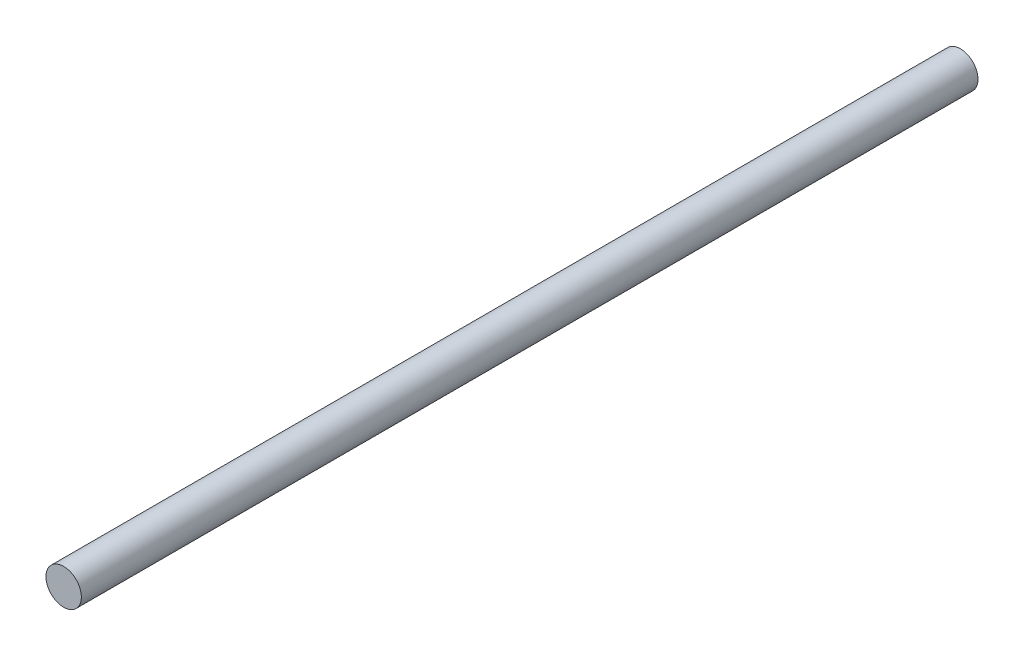
SolidWorks part; units mm, degrees
ref_plane "Front Plane" through (0, 0, 0) normal (0, 0, 1) x (1, 0, 0)
ref_plane "Top Plane" through (0, 0, 0) normal (0, 1, 0) x (1, 0, 0)
ref_plane "Right Plane" through (0, 0, 0) normal (1, 0, 0) x (0, 0, -1)
sketch "Sketch1" plane through (0, 0, 0) normal (0, 0, 1) x (1, 0, 0)
  circle A0 centre (0, 0) radius 0.75
  dimension "D1" = 1.5
extrude "Boss-Extrude1" add sketch "Sketch1" along normal blind 38
